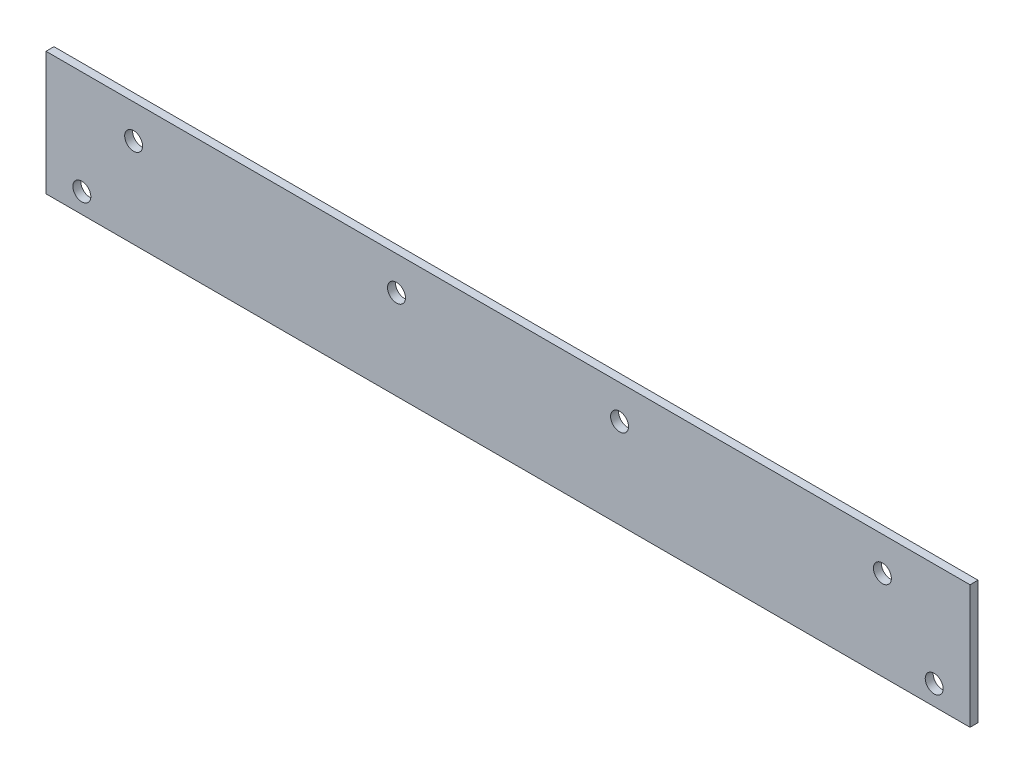
SolidWorks part; units mm, degrees
ref_plane "Спереди" through (0, 0, 0) normal (0, 0, 1) x (1, 0, 0)
ref_plane "Сверху" through (0, 0, 0) normal (0, 1, 0) x (1, 0, 0)
ref_plane "Справа" through (0, 0, 0) normal (1, 0, 0) x (0, 0, -1)
sketch "Эскиз1" plane through (0, 0, 0) normal (0, 0, 1) x (1, 0, 0)
  line L0 (-42.186, 0) -> (41.4926, 0) construction
  line L1 (0, 29.1257) -> (0, -33.0554) construction
  line L2 (-138.8502, 7) -> (139.831, 7) construction
  line L3 (-116, -15.5) -> (116, -15.5)
  line L4 (-116, -15.5) -> (-116, 15.5)
  line L5 (-116, 15.5) -> (116, 15.5)
  line L6 (116, -15.5) -> (116, 15.5)
  line L7 (-107, -10.5) -> (74.8064, -10.5) construction
  circle A0 centre (-28, 7) radius 2.25
  circle A1 centre (28, 7) radius 2.25
  circle A2 centre (-94, 7) radius 2.25
  circle A3 centre (94, 7) radius 2.25
  circle A4 centre (-107, -10.5) radius 2.25
  circle A5 centre (107, -10.5) radius 2.25
  dimension "D3" = 56
  dimension "D5" = 4.5
  dimension "D6" = 66
  dimension "D9" = 4.5
  dimension "D10" = 214
  dimension "D1" = 31
  dimension "D2" = 232
  dimension "D4" = 8.5
  dimension "D7" = 5
extrude "Вытянуть1" add sketch "Эскиз1" along normal blind 2
